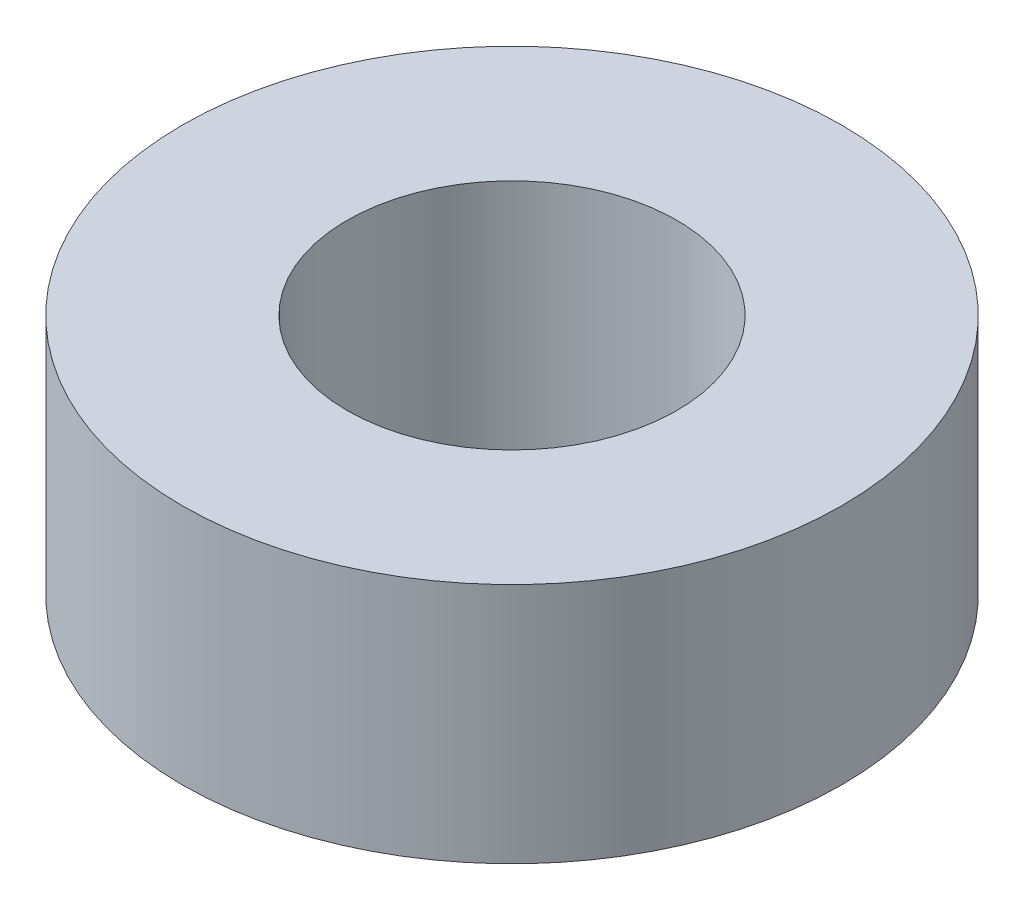
SolidWorks part; units mm, degrees
material "2024-T4"
ref_plane "Front Plane" through (0, 0, 0) normal (0, 0, 1) x (1, 0, 0)
ref_plane "Top Plane" through (0, 0, 0) normal (0, 1, 0) x (1, 0, 0)
ref_plane "Right Plane" through (0, 0, 0) normal (1, 0, 0) x (0, 0, -1)
sketch "Sketch1" plane through (0, 0, 0) normal (0, 1, 0) x (1, 0, 0)
  circle A0 centre (0, 0) radius 150
  circle A1 centre (0, 0) radius 75
  dimension "D1" = 300
  dimension "D2" = 150
extrude "Boss-Extrude1" add sketch "Sketch1" along normal mid plane 110
